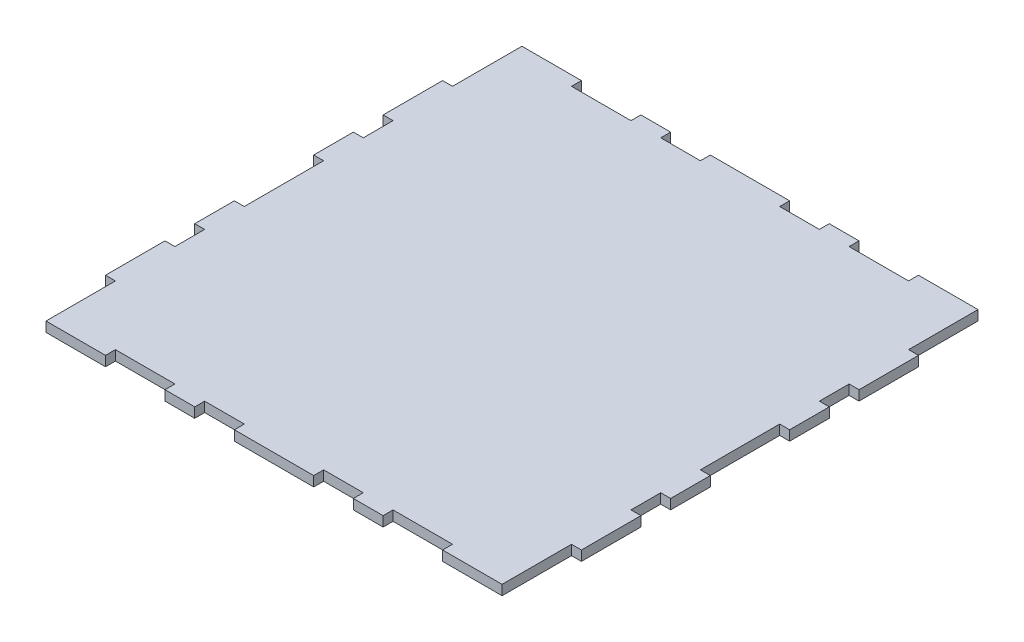
SolidWorks part; units mm, degrees
ref_plane "Front Plane" through (0, 0, 0) normal (0, 0, 1) x (1, 0, 0)
ref_plane "Top Plane" through (0, 0, 0) normal (0, 1, 0) x (1, 0, 0)
ref_plane "Right Plane" through (0, 0, 0) normal (1, 0, 0) x (0, 0, -1)
sketch "Sketch1" plane through (0, 0, 0) normal (0, 1, 0) x (1, 0, 0)
  line L0 (0, 152.4) -> (304.8, 152.4)
  line L1 (0, 0) -> (304.8, 0)
  line L2 (0, 0) -> (0, 304.8)
  line L3 (0, 304.8) -> (304.8, 304.8)
  line L4 (304.8, 0) -> (304.8, 304.8)
  line L5 (152.4, 0) -> (152.4, 304.8)
  line L6 (101.6, 0) -> (127, 0)
  line L7 (101.6, 0) -> (101.6, 6.35)
  line L8 (101.6, 6.35) -> (127, 6.35)
  line L9 (127, 0) -> (127, 6.35)
  line L10 (44.45, 0) -> (82.55, 0)
  line L11 (44.45, 0) -> (44.45, 6.35)
  line L12 (44.45, 6.35) -> (82.55, 6.35)
  line L13 (82.55, 0) -> (82.55, 6.35)
  line L14 (222.25, 0) -> (222.25, 6.35)
  line L15 (260.35, 6.35) -> (222.25, 6.35)
  line L16 (260.35, 0) -> (260.35, 6.35)
  line L17 (260.35, 0) -> (222.25, 0)
  line L18 (177.8, 0) -> (177.8, 6.35)
  line L19 (203.2, 6.35) -> (177.8, 6.35)
  line L20 (203.2, 0) -> (203.2, 6.35)
  line L21 (203.2, 0) -> (177.8, 0)
  line L22 (203.2, 304.8) -> (177.8, 304.8)
  line L23 (203.2, 304.8) -> (203.2, 298.45)
  line L24 (203.2, 298.45) -> (177.8, 298.45)
  line L25 (177.8, 304.8) -> (177.8, 298.45)
  line L26 (260.35, 304.8) -> (222.25, 304.8)
  line L27 (260.35, 304.8) -> (260.35, 298.45)
  line L28 (260.35, 298.45) -> (222.25, 298.45)
  line L29 (222.25, 304.8) -> (222.25, 298.45)
  line L30 (82.55, 304.8) -> (82.55, 298.45)
  line L31 (44.45, 298.45) -> (82.55, 298.45)
  line L32 (44.45, 304.8) -> (44.45, 298.45)
  line L33 (44.45, 304.8) -> (82.55, 304.8)
  line L34 (127, 304.8) -> (127, 298.45)
  line L35 (101.6, 298.45) -> (127, 298.45)
  line L36 (101.6, 304.8) -> (101.6, 298.45)
  line L37 (101.6, 304.8) -> (127, 304.8)
  line L38 (6.35, 203.2) -> (6.35, 222.25)
  line L39 (0, 0) -> (6.35, 0)
  line L40 (0, 0) -> (0, 44.45)
  line L41 (0, 44.45) -> (6.35, 44.45)
  line L42 (6.35, 0) -> (6.35, 44.45)
  line L43 (0, 101.6) -> (6.35, 101.6)
  line L44 (0, 101.6) -> (0, 82.55)
  line L45 (0, 82.55) -> (6.35, 82.55)
  line L46 (6.35, 101.6) -> (6.35, 82.55)
  line L47 (0, 222.25) -> (6.35, 222.25)
  line L48 (0, 203.2) -> (0, 222.25)
  line L49 (0, 203.2) -> (6.35, 203.2)
  line L50 (6.35, 304.8) -> (6.35, 260.35)
  line L51 (0, 260.35) -> (6.35, 260.35)
  line L52 (0, 304.8) -> (0, 260.35)
  line L53 (0, 304.8) -> (6.35, 304.8)
  line L54 (304.8, 304.8) -> (298.45, 304.8)
  line L55 (304.8, 304.8) -> (304.8, 260.35)
  line L56 (304.8, 260.35) -> (298.45, 260.35)
  line L57 (298.45, 304.8) -> (298.45, 260.35)
  line L58 (304.8, 203.2) -> (298.45, 203.2)
  line L59 (304.8, 203.2) -> (304.8, 222.25)
  line L60 (304.8, 222.25) -> (298.45, 222.25)
  line L61 (298.45, 101.6) -> (298.45, 82.55)
  line L62 (304.8, 82.55) -> (298.45, 82.55)
  line L63 (304.8, 101.6) -> (304.8, 82.55)
  line L64 (304.8, 101.6) -> (298.45, 101.6)
  line L65 (298.45, 0) -> (298.45, 44.45)
  line L66 (304.8, 44.45) -> (298.45, 44.45)
  line L67 (304.8, 0) -> (304.8, 44.45)
  line L68 (304.8, 0) -> (298.45, 0)
  line L69 (298.45, 203.2) -> (298.45, 222.25)
  line L70 (304.8, 0) -> (304.8, 304.8)
  line L71 (0, 177.8) -> (6.35, 177.8)
  line L72 (0, 127) -> (6.35, 127)
  line L73 (0, 127) -> (0, 177.8)
  line L74 (0, 152.4) -> (6.35, 152.4)
  line L75 (6.35, 127) -> (6.35, 177.8)
  line L76 (298.45, 127) -> (298.45, 177.8)
  line L77 (304.8, 152.4) -> (298.45, 152.4)
  line L78 (304.8, 127) -> (304.8, 177.8)
  line L79 (304.8, 127) -> (298.45, 127)
  line L80 (304.8, 177.8) -> (298.45, 177.8)
  dimension "D1" = 304.8
  dimension "D2" = 304.8
  dimension "D3" = 6.35
  dimension "D4" = 25.4
  dimension "D5" = 101.6
  dimension "D6" = 6.35
  dimension "D7" = 44.45
  dimension "D8" = 6.35
  dimension "D9" = 44.45
  dimension "D10" = 6.35
  dimension "D11" = 19.05
  dimension "D12" = 38.1
  dimension "D13" = 38.1
  dimension "D14" = 6.35
  dimension "D15" = 25.4
extrude "Boss-Extrude1" add sketch "Sketch1" along normal blind 6.35 contours L75 L72 L2 L43 L46 L45 L41 L42 L1 L11 L12 L13 L7 L8 L9 L5 L0 | L75 L0 L5 L3 L34 L35 L36 L30 L31 L32 L50 L51 L2 L47 L38 L49 L71 | L80 L70 L58 L69 L60 L4 L56 L57 L3 L27 L28 L29 L23 L24 L25 L5 L0 L76 | L4 L79 L76 L0 L5 L1 L18 L19 L20 L14 L15 L16 L65 L66 L62 L61 L64
